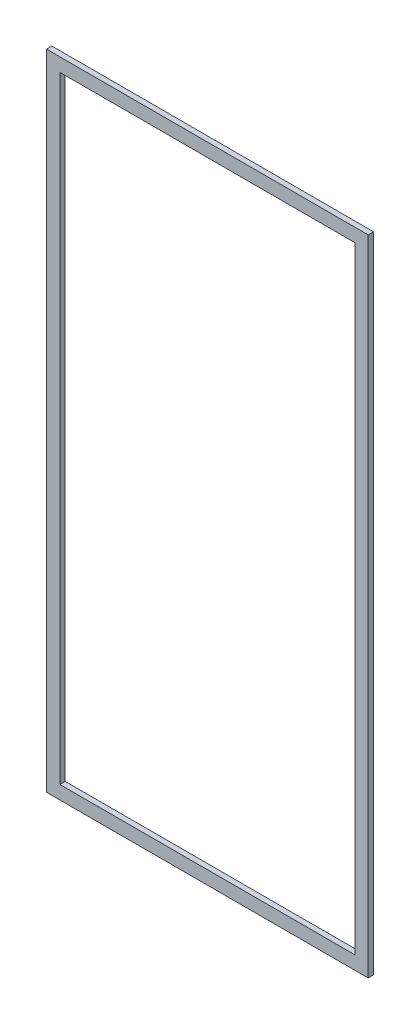
SolidWorks part; units mm, degrees
ref_plane "Front Plane" through (0, 0, 0) normal (0, 0, 1) x (1, 0, 0)
ref_plane "Top Plane" through (0, 0, 0) normal (0, 1, 0) x (1, 0, 0)
ref_plane "Right Plane" through (0, 0, 0) normal (1, 0, 0) x (0, 0, -1)
sketch "Sketch1" plane through (0, 0, 0) normal (0, 0, 1) x (1, 0, 0)
  line L1 (300, -600) -> (-300, -600)
  line L2 (300, -600) -> (300, 600)
  line L3 (300, 600) -> (-300, 600)
  line L4 (-300, -600) -> (-300, 600)
  line L5 (300, -600) -> (-300, 600) construction
  line L6 (300, 600) -> (-300, -600) construction
  line L7 (275, -575) -> (-275, -575)
  line L8 (275, -575) -> (275, 575)
  line L9 (275, 575) -> (-275, 575)
  line L10 (-275, -575) -> (-275, 575)
  line L11 (275, -575) -> (-275, 575) construction
  line L12 (275, 575) -> (-275, -575) construction
  point P0 (0, 0)
  point P6 (0, 0)
extrude "Boss-Extrude1" add sketch "Sketch1" along normal blind 10
